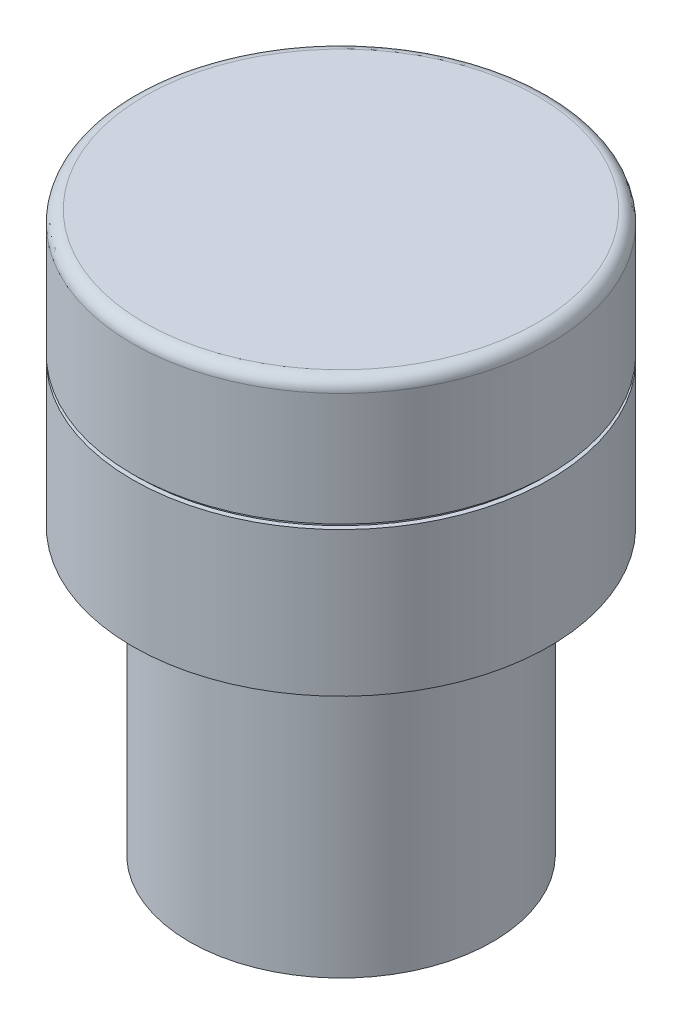
SolidWorks part; units mm, degrees
ref_plane "Front Plane" through (0, 0, 0) normal (0, 0, 1) x (1, 0, 0)
ref_plane "Top Plane" through (0, 0, 0) normal (0, 1, 0) x (1, 0, 0)
ref_plane "Right Plane" through (0, 0, 0) normal (1, 0, 0) x (0, 0, -1)
ref_plane "Plane1" through (0, 0, 0) normal (0, 1, 0) x (1, 0, 0)
sketch "Sketch1" plane through (0, 0, 0) normal (0, 1, 0) x (1, 0, 0)
  circle A0 centre (0, 0) radius 8
extrude "Extrude1" add sketch "Sketch1" along normal blind 15
sketch "Sketch2" plane through (0, 15, 0) normal (0, 1, 0) x (-1, 0, 0)
  circle A0 centre (0, 0) radius 11
extrude "Extrude2" add sketch "Sketch2" along normal blind 7.62
sketch "Sketch3" plane through (0, 22.62, 0) normal (0, 1, 0) x (-1, 0, 0)
  circle A0 centre (0, 0) radius 10.75
extrude "Extrude3" add sketch "Sketch3" along normal blind 0.25
sketch "Sketch4" plane through (0, 22.87, 0) normal (0, 1, 0) x (-1, 0, 0)
  circle A0 centre (0, 0) radius 11
extrude "Extrude4" add sketch "Sketch4" along normal blind 6.604
fillet "Fillet1" radius 0.635 1 edges at (0, 29.474, 11)
